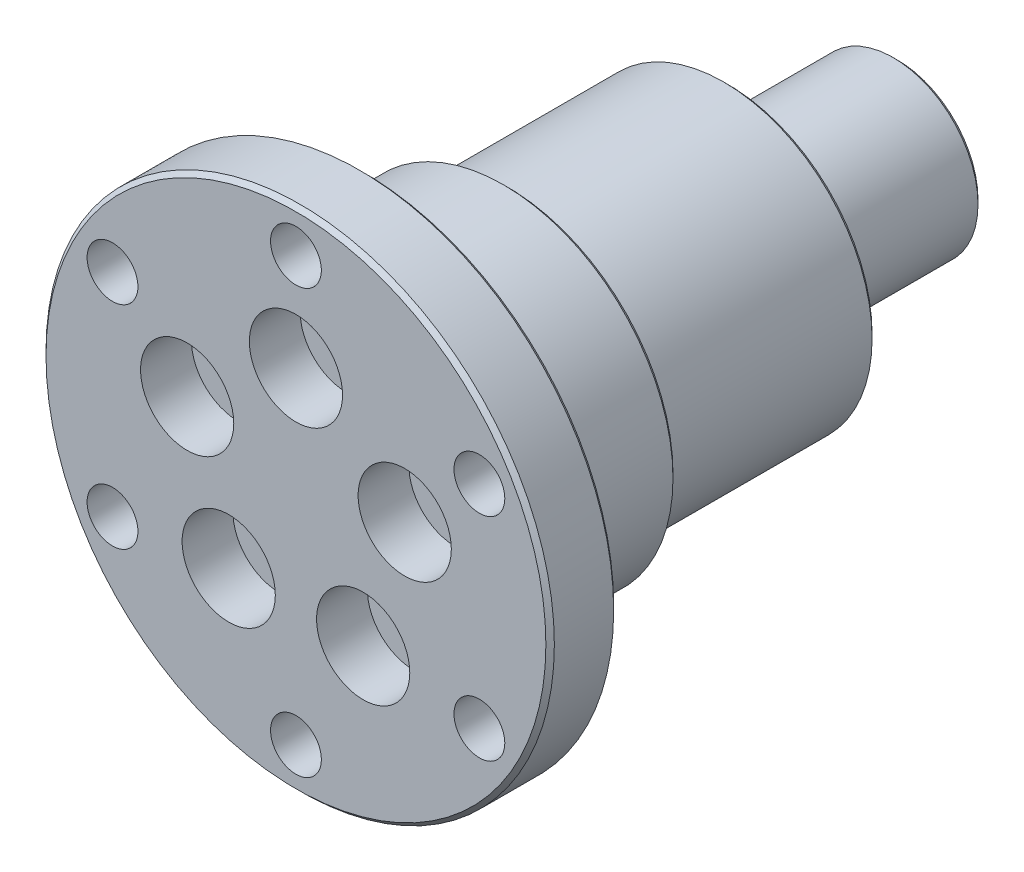
SolidWorks part; units mm, degrees
ref_plane "前视基准面" through (0, 0, 0) normal (0, 0, 1) x (1, 0, 0)
ref_plane "上视基准面" through (0, 0, 0) normal (0, 1, 0) x (1, 0, 0)
ref_plane "右视基准面" through (0, 0, 0) normal (1, 0, 0) x (0, 0, -1)
sketch "草图1" plane through (0, 0, 0) normal (0, 0, 1) x (1, 0, 0)
  circle A0 centre (0, 0) radius 10
extrude "拉伸1" add sketch "草图1" along normal blind 20
sketch "草图2" plane through (0, 0, 20) normal (0, 0, 1) x (1, 0, 0)
  circle A0 centre (0, 0) radius 17.5
extrude "拉伸2" add sketch "草图2" along normal blind 41
sketch "草图3" plane through (0, 0, 61) normal (0, 0, 1) x (1, 0, 0)
  circle A0 centre (0, 0) radius 17.5
  dimension "D1" = 35
extrude "拉伸3" add sketch "草图3" along normal blind 10
sketch "草图8" plane through (0, 0, 71) normal (0, 0, 1) x (1, 0, 0)
  circle A0 centre (12.8393, 4.1717) radius 3
  circle A1 centre (0, 13.5) radius 3
  circle A2 centre (7.9351, -10.9217) radius 3
  circle A3 centre (-7.9351, -10.9217) radius 3
  circle A4 centre (-12.8393, 4.1717) radius 3
extrude "切除-拉伸4" cut sketch "草图8" against normal blind 60
sketch "草图9" plane through (0, 0, 71) normal (0, 0, 1) x (1, 0, 0)
  circle A0 centre (0, 0) radius 30
  circle A1 centre (0, 0) radius 17.5
extrude "拉伸4" add sketch "草图9" against normal blind 8
sketch "草图10" plane through (0, 0, 63) normal (0, 0, -1) x (-1, 0, 0)
  circle A0 centre (0, 0) radius 20
  circle A1 centre (0, 0) radius 17.5
extrude "拉伸5" add sketch "草图10" along normal blind 17
chamfer "倒角1" distance 0.5 angle 45 1 edges at (17.5, 0, 20)
chamfer "倒角2" distance 0.5 angle 45 4 edges at (10, 0, 0) (-20, 0, 46) (30, 0, 63) (30, 0, 71)
sketch "草图12" plane through (0, 0, 71) normal (0, 0, 1) x (1, 0, 0)
  circle A0 centre (0, 13.5) radius 5.5
  circle A1 centre (12.8393, 4.1717) radius 5.5
  circle A2 centre (7.9351, -10.9217) radius 5.5
  circle A3 centre (-7.9351, -10.9217) radius 5.5
  circle A4 centre (-12.8393, 4.1717) radius 5.5
extrude "切除-拉伸6" cut sketch "草图12" against normal blind 6
sketch "草图13" plane through (0, 0, 71) normal (0, 0, 1) x (1, 0, 0)
  circle A1 centre (0, 25) radius 3
  circle A2 centre (21.6506, 12.5) radius 3
  circle A3 centre (21.6506, -12.5) radius 3
  circle A4 centre (0, -25) radius 3
  circle A5 centre (-21.6506, -12.5) radius 3
  circle A6 centre (-21.6506, 12.5) radius 3
extrude "切除-拉伸7" cut sketch "草图13" against normal blind 8
